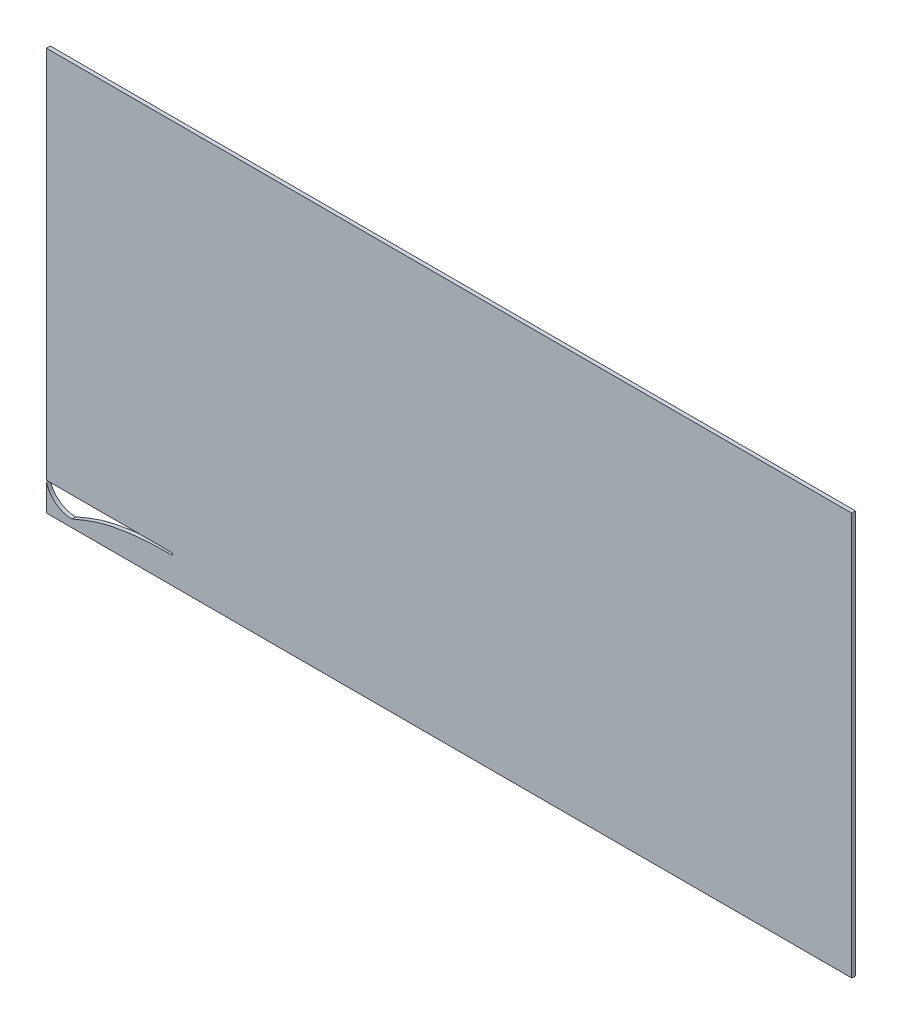
SolidWorks part; units mm, degrees
ref_plane "Front Plane" through (0, 0, 0) normal (0, 0, 1) x (1, 0, 0)
ref_plane "Top Plane" through (0, 0, 0) normal (0, 1, 0) x (1, 0, 0)
ref_plane "Right Plane" through (0, 0, 0) normal (1, 0, 0) x (0, 0, -1)
curve "Curve1"
  spline degree 3 poles (0, 1000, 0) (291.7659, 1123.3225, 0) (781.5223, 1330.3308, 0) (1362.8974, 1573.6532, 0) (1725.5806, 1720.7706, 0) (1954.5714, 1810.9264, 0) (2153.7007, 1887.0782, 0) (2340.1132, 1956.2786, 0) (2520.5687, 2021.2692, 0) (2698.6315, 2083.4416, 0) (2876.4968, 2143.6056, 0) (3055.666, 2202.2707, 0) (3237.2506, 2259.7736, 0) (3422.1263, 2316.3428, 0) (3611.0201, 2372.135, 0) (3804.562, 2427.2562, 0) (4003.318, 2481.7751, 0) (4207.8116, 2535.732, 0) (4418.5393, 2589.1442, 0) (4635.9812, 2642.01, 0) (4860.609, 2694.3115, 0) (5092.8922, 2746.016, 0) (5333.3029, 2797.0778, 0) (5582.32, 2847.4384, 0) (5840.4324, 2897.0272, 0) (6108.142, 2945.7616, 0) (6385.9663, 2993.5472, 0) (6674.4407, 3040.2773, 0) (6974.1213, 3085.8325, 0) (7285.5862, 3130.0805, 0) (7609.4387, 3172.8757, 0) (7946.3085, 3214.0576, 0) (8296.8545, 3253.4511, 0) (8661.767, 3290.8647, 0) (9041.7694, 3326.0899, 0) (9437.6214, 3358.9, 0) (9850.1208, 3389.049, 0) (10280.1065, 3416.2693, 0) (10728.4608, 3440.2731, 0) (11196.1131, 3460.74, 0) (11684.0418, 3477.3584, 0) (12193.2785, 3489.6504, 0) (12724.9111, 3497.6601, 0) (13086.925, 3498.665, 0) (13271.8436, 3499.1783, 0) knots 0 0 0 0 0.069756 0.117091 0.138787 0.155944 0.171285 0.185735 0.199731 0.213523 0.227268 0.24108 0.255039 0.269213 0.283655 0.298413 0.313528 0.32904 0.344986 0.361401 0.378319 0.395775 0.413804 0.432441 0.451722 0.471683 0.492363 0.513801 0.536037 0.559115 0.583078 0.607974 0.63385 0.660759 0.688754 0.717891 0.74823 0.779834 0.812769 0.847104 0.882915 0.920279 0.959278 1 1 1 1
sketch "Sketch1" plane through (0, 0, 0) normal (0, 0, 1) x (1, 0, 0)
  line L1 (-3353.8569, 3499.1783) -> (-3353.8569, 0)
  line L2 (-3353.8569, 0) -> (102806.1431, 0)
  line L3 (102806.1431, 0) -> (102806.1431, 53080)
  line L4 (102806.1431, 53080) -> (-3353.8569, 53080)
  line L5 (-3353.8569, 53080) -> (-3353.8569, 3749.1783)
  line L6 (-3353.8569, 3749.1783) -> (13271.8436, 3749.1783)
  line L7 (13271.8436, 3749.1783) -> (13271.8436, 3499.1783)
  arc A0 (0, 1000) -> (-3353.8569, 3499.1783) centre (0, 4500) cw
  spline S0 degree 3 poles (-2771.1758, -148.6032) (-1547.6185, 338.6652) (-140.8507, 944.291) (1362.8974, 1573.6532) (1725.5806, 1720.7706) (1954.5714, 1810.9264) (2153.7007, 1887.0782) (2340.1132, 1956.2786) (2520.5687, 2021.2692) (2698.6315, 2083.4416) (2876.4968, 2143.6056) (3055.666, 2202.2707) (3237.2506, 2259.7736) (3422.1263, 2316.3428) (3611.0201, 2372.135) (3804.562, 2427.2562) (4003.318, 2481.7751) (4207.8116, 2535.732) (4418.5393, 2589.1442) (4635.9812, 2642.01) (4860.609, 2694.3115) (5092.8922, 2746.016) (5333.3029, 2797.0778) (5582.32, 2847.4384) (5840.4324, 2897.0272) (6108.142, 2945.7616) (6385.9663, 2993.5472) (6674.4407, 3040.2773) (6974.1213, 3085.8325) (7285.5862, 3130.0805) (7609.4387, 3172.8757) (7946.3085, 3214.0576) (8296.8545, 3253.4511) (8661.767, 3290.8647) (9041.7694, 3326.0899) (9437.6214, 3358.9) (9850.1208, 3389.049) (10280.1065, 3416.2693) (10728.4608, 3440.2731) (11196.1131, 3460.74) (11684.0418, 3477.3584) (12193.2785, 3489.6504) (13721.9421, 3512.6816) (15081.4323, 3470.4496) (16261.8263, 3689.4758) knots -0.220191 -0.220191 -0.220191 -0.220191 0.069756 0.117091 0.138787 0.155944 0.171285 0.185735 0.199731 0.213523 0.227268 0.24108 0.255039 0.269213 0.283655 0.298413 0.313528 0.32904 0.344986 0.361401 0.378319 0.395775 0.413804 0.432441 0.451722 0.471683 0.492363 0.513801 0.536037 0.559115 0.583078 0.607974 0.63385 0.660759 0.688754 0.717891 0.74823 0.779834 0.812769 0.847104 0.882915 0.920279 0.959278 1.219582 1.219582 1.219582 1.219582 only from (0, 1000) to (13271.8436, 3499.1783) construction
  spline S1 degree 3 poles (0, 1000) (291.7659, 1123.3225) (781.5223, 1330.3308) (1362.8974, 1573.6532) (1725.5806, 1720.7706) (1954.5714, 1810.9264) (2153.7007, 1887.0782) (2340.1132, 1956.2786) (2520.5687, 2021.2692) (2698.6315, 2083.4416) (2876.4968, 2143.6056) (3055.666, 2202.2707) (3237.2506, 2259.7736) (3422.1263, 2316.3428) (3611.0201, 2372.135) (3804.562, 2427.2562) (4003.318, 2481.7751) (4207.8116, 2535.732) (4418.5393, 2589.1442) (4635.9812, 2642.01) (4860.609, 2694.3115) (5092.8922, 2746.016) (5333.3029, 2797.0778) (5582.32, 2847.4384) (5840.4324, 2897.0272) (6108.142, 2945.7616) (6385.9663, 2993.5472) (6674.4407, 3040.2773) (6974.1213, 3085.8325) (7285.5862, 3130.0805) (7609.4387, 3172.8757) (7946.3085, 3214.0576) (8296.8545, 3253.4511) (8661.767, 3290.8647) (9041.7694, 3326.0899) (9437.6214, 3358.9) (9850.1208, 3389.049) (10280.1065, 3416.2693) (10728.4608, 3440.2731) (11196.1131, 3460.74) (11684.0418, 3477.3584) (12193.2785, 3489.6504) (12724.9111, 3497.6601) (13086.925, 3498.665) (13271.8436, 3499.1783) knots 0 0 0 0 0.069756 0.117091 0.138787 0.155944 0.171285 0.185735 0.199731 0.213523 0.227268 0.24108 0.255039 0.269213 0.283655 0.298413 0.313528 0.32904 0.344986 0.361401 0.378319 0.395775 0.413804 0.432441 0.451722 0.471683 0.492363 0.513801 0.536037 0.559115 0.583078 0.607974 0.63385 0.660759 0.688754 0.717891 0.74823 0.779834 0.812769 0.847104 0.882915 0.920279 0.959278 1 1 1 1
  dimension "D1" = 3500
  dimension "D2" = 250
  dimension "D3" = 106160
  dimension "D4" = 53080
extrude "Boss-Extrude1" add sketch "Sketch1" along normal blind 500
